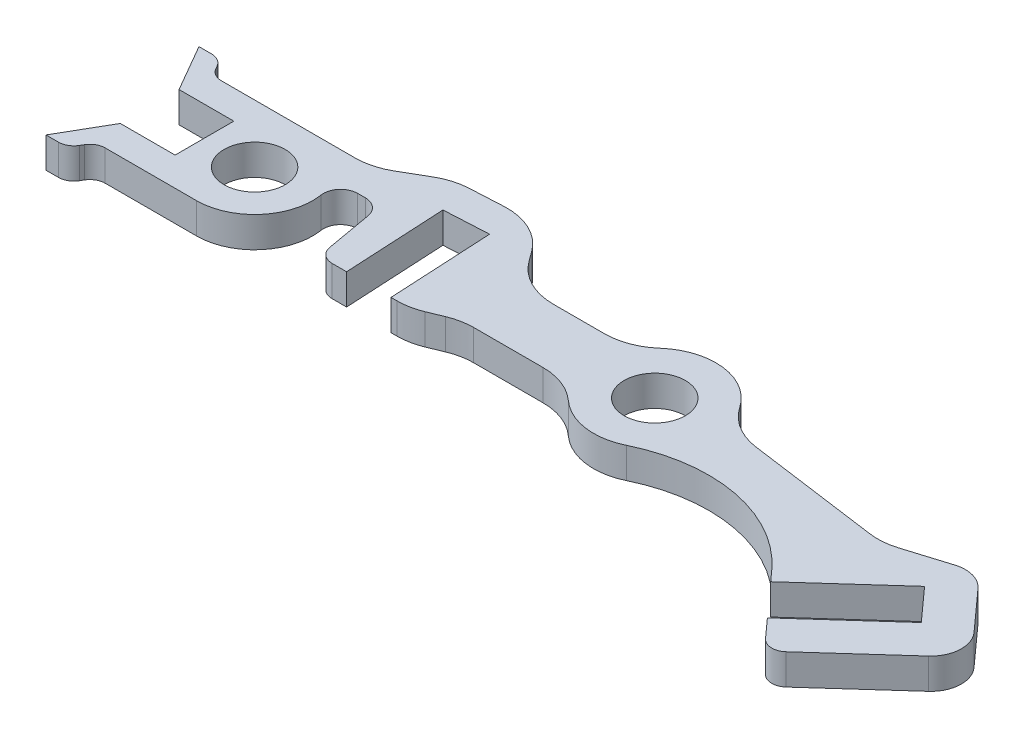
SolidWorks part; units mm, degrees
ref_plane "前视基准面" through (0, 0, 0) normal (0, 0, 1) x (1, 0, 0)
ref_plane "上视基准面" through (0, 0, 0) normal (0, 1, 0) x (1, 0, 0)
ref_plane "右视基准面" through (0, 0, 0) normal (1, 0, 0) x (0, 0, -1)
sketch "草图1" plane through (0, 0, 0) normal (0, 1, 0) x (1, 0, 0)
  line L0 (-65.4, 0) -> (0, 0) construction
  circle A0 centre (0, 0) radius 5
  circle A1 centre (-65.4, 0) radius 5
  dimension "D1" = 10
  dimension "D2" = 10
  dimension "D3" = 65.4
sketch "草图3" plane through (0, 0, 0) normal (0, 1, 0) x (1, 0, 0)
  line L0 (-35.1038, -20.7582) -> (-36.7, 9.7)
  line L1 (-35.1038, -20.7582) -> (-42.3438, -21.1376)
  line L2 (-36.7, 9.7) -> (-43.9401, 9.3206)
  line L3 (-42.3438, -21.1376) -> (-43.9401, 9.3206)
  line L4 (-36.7, 9.7) -> (-36.7, -40.2194) construction
  line L5 (-65.4, 0) -> (0, 0) construction
  line L6 (53.5512, -9.9878) -> (30.8853, -30.3963)
  line L7 (53.5512, -9.9878) -> (48.7, -4.6)
  line L8 (30.8853, -30.3963) -> (26.0341, -25.0085)
  line L9 (48.7, -4.6) -> (26.0341, -25.0085)
  line L10 (0, 0) -> (96.2024, 0) construction
  line L11 (48.7, 37.3282) -> (48.7, -37.0287) construction
  dimension "D1" = 7.25
  dimension "D2" = 30.5
  dimension "D3" = 36.7
  dimension "D4" = 3
  dimension "D5" = 9.7
  dimension "D6" = 30.5
  dimension "D7" = 7.25
  dimension "D8" = 48.7
  dimension "D9" = 4.6
  dimension "D10" = 42
sketch "草图2" plane through (0, 0, 0) normal (0, 1, 0) x (1, 0, 0)
  line L0 (0, 0) -> (-90, 0) construction
  line L1 (-73.5982, 4.8) -> (-73.5982, -4.8)
  line L2 (-73.5982, -4.8) -> (-82.5544, -4.8)
  line L3 (-82.5544, -4.8) -> (-87, -12.5)
  line L4 (-87, -12.5) -> (-83.5, -12.5)
  line L5 (-83.5, -12.5) -> (-82.4896, -10.75)
  line L6 (-80.3246, -9.5) -> (-65.4, -9.5)
  line L7 (-83.5, 12.5) -> (-82.4896, 10.75)
  line L8 (-80.3246, 9.5) -> (-65.4, 9.5)
  line L9 (-87, 12.5) -> (-83.5, 12.5)
  line L10 (-82.5544, 4.8) -> (-87, 12.5)
  line L11 (-73.5982, 4.8) -> (-82.5544, 4.8)
  line L12 (-65.4, 9.5) -> (-55.8, 9.5)
  line L13 (-55.8, 9.5) -> (-47.313, 14.4)
  line L14 (-47.313, 14.4) -> (-34.0312, 15.0961)
  line L15 (-34.0312, 15.0961) -> (-26.6597, 5.001)
  line L16 (-26.6597, 5.001) -> (-8.6597, 5.001)
  line L17 (9.777, 2.1) -> (39, -1.9332)
  line L18 (39, -1.9332) -> (51.2314, 1.8394)
  line L19 (51.2314, 1.8394) -> (62.6066, -10.794)
  line L20 (62.6066, -10.794) -> (44.7711, -26.8532)
  line L21 (44.7711, -26.8532) -> (33.8753, -14.7521)
  line L23 (-26.7727, -4.8) -> (-8.7727, -4.8)
  line L24 (-26.7727, -4.8) -> (-32.8282, -7.3)
  line L25 (-32.8282, -7.3) -> (-47.5282, -7.3)
  line L26 (-47.5282, -7.3) -> (-49.6441, 4.7)
  line L27 (-49.6441, 4.7) -> (-57.1441, 4.7)
  line L28 (53.5512, -9.9878) -> (30.8853, -30.3963) construction
  line L29 (-36.7, 9.7) -> (-43.9401, 9.3206) construction
  arc A0 (-8.7727, -4.8) -> (4.3705, -8.9944) centre (0, 0) ccw
  arc A1 (-73.5982, -4.8) -> (-73.5982, 4.8) centre (-65.4, 0) ccw construction
  arc A2 (-82.4896, -10.75) -> (-80.3246, -9.5) centre (-80.3246, -12) cw
  arc A3 (-82.4896, 10.75) -> (-80.3246, 9.5) centre (-80.3246, 12) ccw
  arc A4 (33.8753, -14.7521) -> (4.3705, -8.9944) centre (15.2966, -31.4804) ccw
  arc A5 (9.777, 2.1) -> (-8.6597, 5.001) centre (0, 0) ccw
  arc A6 (-65.4, -9.5) -> (-65.4, 9.5) centre (-65.4, 0) ccw
  circle A7 centre (-65.4, 0) radius 5 construction
  circle A8 centre (0, 0) radius 5 construction
  circle A9 centre (-65.4, 0) radius 5
  circle A10 centre (0, 0) radius 5
  point P47 (-73.5982, 0)
  dimension "D1" = 20
  dimension "D2" = 19
  dimension "D9" = 2.5
  dimension "D29" = 25
  dimension "D3" = 90
  dimension "D4" = 87
  dimension "D5" = 12.5
  dimension "D6" = 4.8
  dimension "D7" = 60
  dimension "D8" = 3.5
  dimension "D10" = 9.6
  dimension "D11" = 13.3
  dimension "D12" = 12.5
  dimension "D13" = 18
  dimension "D14" = 9.8
  dimension "D15" = 4.7
  dimension "D16" = 12
  dimension "D17" = 100
  dimension "D18" = 7.5
  dimension "D19" = 14.7
  dimension "D20" = 18
  dimension "D21" = 4.8
  dimension "D22" = 29.5
  dimension "D23" = 39
  dimension "D24" = 2.1
  dimension "D25" = 12.8
  dimension "D26" = 155
  dimension "D27" = 17
  dimension "D28" = 24
extrude "凸台-拉伸1" add sketch "草图2" against normal blind 5 contours A6 L27 L26 L25 L24 L23 A0 A4 L21 L20 L19 L18 L17 A5 L16 L15 L14 L13 L12 A10 | L6 A6 L8 A3 L7 L9 L10 L11 L1 L2 L3 L4 L5 A2 A9
sketch "草图4" plane through (0, -5, 0) normal (0, -1, 0) x (-1, 0, 0)
  line L0 (42.3438, -21.1376) -> (43.9401, 9.3206) construction
  line L1 (36.7, 9.7) -> (43.9401, 9.3206) construction
  line L2 (35.1038, -20.7582) -> (36.7, 9.7) construction
  line L3 (35.1038, -20.7582) -> (42.3438, -21.1376) construction
  line L4 (-48.7, -4.6) -> (-26.0341, -25.0085) construction
  line L5 (-30.8853, -30.3963) -> (-26.0341, -25.0085) construction
  line L6 (-53.5512, -9.9878) -> (-30.8853, -30.3963) construction
  line L7 (-53.5512, -9.9878) -> (-48.7, -4.6) construction
  line L8 (42.3438, -21.1376) -> (43.9401, 9.3206)
  line L9 (36.7, 9.7) -> (43.9401, 9.3206)
  line L10 (35.1038, -20.7582) -> (36.7, 9.7)
  line L11 (35.1038, -20.7582) -> (42.3438, -21.1376)
  line L12 (-48.7, -4.6) -> (-26.0341, -25.0085)
  line L13 (-30.8853, -30.3963) -> (-26.0341, -25.0085)
  line L14 (-53.5512, -9.9878) -> (-30.8853, -30.3963)
  line L15 (-53.5512, -9.9878) -> (-48.7, -4.6)
extrude "切除-拉伸1" cut sketch "草图4" against normal through all
fillet "圆角1" radius 2.8 1 edges at (-57.1441, -2.5, -4.7)
fillet "圆角2" radius 2.8 1 edges at (-49.6441, -2.5, -4.7)
fillet "圆角3" radius 10 9 edges at (39, -2.5, 1.9332) (-32.8282, -2.5, 7.3) (-26.7727, -2.5, 4.8) (-8.7727, -2.5, 4.8) (9.777, -2.5, -2.1) (-8.6597, -2.5, -5.001) (-26.6597, -2.5, -5.001) (-47.313, -2.5, -14.4) (-34.0312, -2.5, -15.0961)
fillet "圆角4" radius 5 2 edges at (51.2314, -2.5, -1.8394) (62.6066, -2.5, 10.794)
fillet "圆角5" radius 2.5 4 edges at (-83.5, -2.5, 12.5) (-83.5, -2.5, -12.5) (-47.5282, -2.5, 7.3) (44.7711, -2.5, 26.8532)
fillet "圆角6" radius 10 1 edges at (-55.8, -2.5, -9.5)
